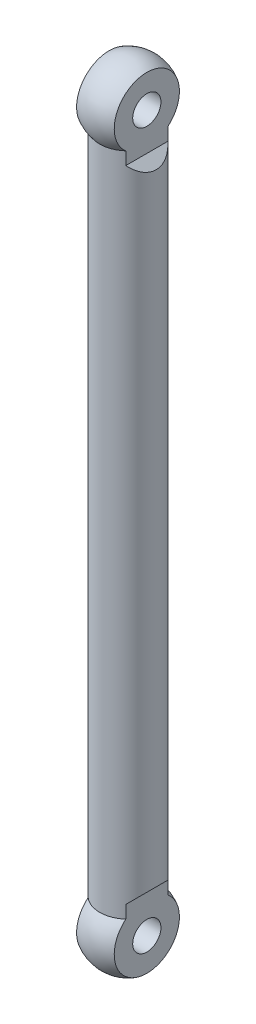
SolidWorks part; units mm, degrees
ref_plane "前视基准面" through (0, 0, 0) normal (0, 0, 1) x (1, 0, 0)
ref_plane "上视基准面" through (0, 0, 0) normal (0, 1, 0) x (1, 0, 0)
ref_plane "右视基准面" through (0, 0, 0) normal (1, 0, 0) x (0, 0, -1)
sketch "草图1" plane through (0, 0, 0) normal (1, 0, 0) x (0, 0, -1)
  line L0 (0, 0) -> (0, 76) construction
  line L1 (3, 2.6458) -> (3, 73.3542)
  line L2 (0, 76) -> (0, 86.2776) construction
  line L3 (0, 0) -> (0, -9.9252) construction
  line L4 (0, -4) -> (0, 80)
  arc A0 (0, -4) -> (3, 2.6458) centre (0, 0) ccw
  arc A1 (3, 73.3542) -> (0, 80) centre (0, 76) ccw
  dimension "D2" = 8
  dimension "D3" = 8
  dimension "D1" = 76
  dimension "D4" = 6
revolve "旋转1" add sketch "草图1" angle 360 about L4
sketch "草图2" plane through (0, 0, 0) normal (0, 0, 1) x (1, 0, 0)
  line L0 (0, 0) -> (0, 76) construction
  line L1 (2, 81) -> (2, 72)
  line L2 (2, 72) -> (3, 71)
  line L3 (3, 2.6458) -> (3, 73.3542) construction
  line L4 (3, 71) -> (8, 71)
  line L5 (8, 71) -> (8, 81)
  line L6 (8, 81) -> (2, 81)
  line L7 (0, 38) -> (25.6817, 38) construction
  line L8 (8, -5) -> (2, -5)
  line L9 (8, 5) -> (8, -5)
  line L10 (3, 5) -> (8, 5)
  line L11 (2, 4) -> (3, 5)
  line L12 (2, -5) -> (2, 4)
  arc A0 (3, 73.3542) -> (-3, 73.3542) centre (0, 76) ccw construction
  dimension "D1" = 2
  dimension "D2" = 45
  dimension "D3" = 34
  dimension "D4" = 10
  dimension "D5" = 5
extrude "切除-拉伸1" cut sketch "草图2" against normal through all both and the other way through all
mirror "镜向1" about plane through (0, 0, 0) normal (1, 0, 0) of "切除-拉伸1"
sketch "草图3" plane through (2, 0, 0) normal (1, 0, 0) x (0, 0, -1)
  circle A0 centre (0, 76) radius 1.5
  circle A1 centre (0, 0) radius 1.5
  arc A2 (2.2361, 73.3542) -> (-2.2361, 73.3542) centre (0, 76) ccw construction
  dimension "D1" = 3
extrude "切除-拉伸2" cut sketch "草图3" against normal through all
move or copy body "实体-移动/复制1" [suppressed] bodies to move or copy 109
